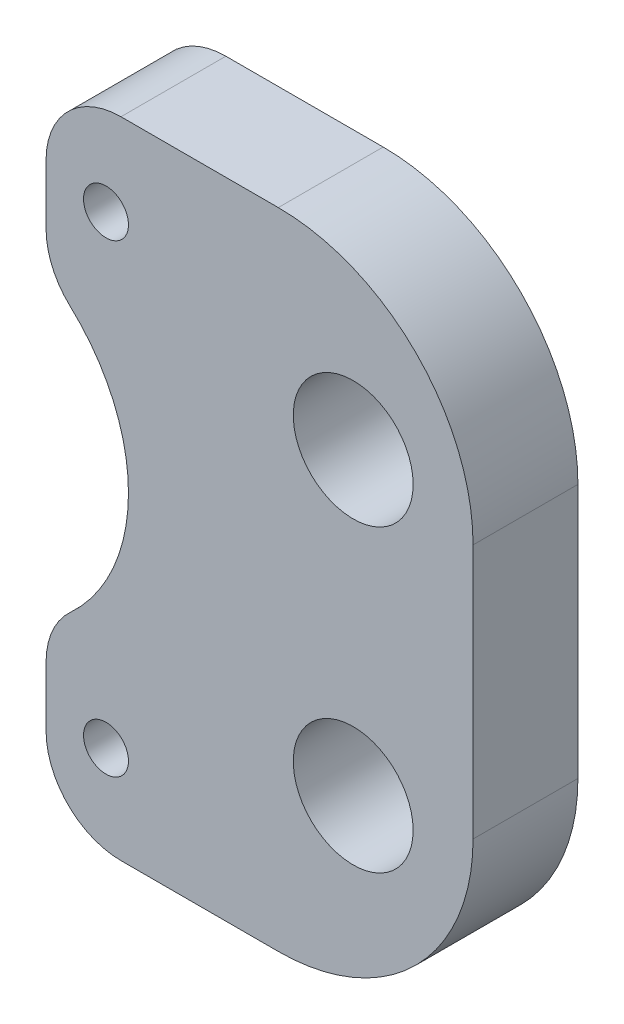
SolidWorks part; units mm, degrees
ref_plane "Alzado" through (0, 0, 0) normal (0, 0, 1) x (1, 0, 0)
ref_plane "Planta" through (0, 0, 0) normal (0, 1, 0) x (1, 0, 0)
ref_plane "Vista lateral" through (0, 0, 0) normal (1, 0, 0) x (0, 0, -1)
sketch "Croquis1" plane through (0, 0, 0) normal (0, 0, 1) x (1, 0, 0)
  line L0 (5, 0) -> (15.5, 0)
  line L1 (28.5, 13) -> (28.5, 30)
  line L2 (15.5, 43) -> (5, 43)
  line L3 (0, 34.02) -> (0, 38)
  line L5 (0, 5) -> (0, 8.98)
  arc A0 (1.6176, 12.6624) -> (1.6176, 30.3376) centre (-6.5, 21.5) ccw
  circle A1 centre (20.5, 31.5) radius 4
  circle A2 centre (20.5, 11.5) radius 4
  circle A3 centre (4, 37) radius 1.5
  circle A4 centre (4, 6) radius 1.5
  arc A5 (1.6176, 30.3376) -> (0, 34.02) centre (5, 34.02) cw
  arc A6 (0, 8.98) -> (1.6176, 12.6624) centre (5, 8.98) cw
  arc A7 (28.5, 13) -> (15.5, 0) centre (15.5, 13) cw
  arc A8 (28.5, 30) -> (15.5, 43) centre (15.5, 30) ccw
  arc A9 (5, 43) -> (0, 38) centre (5, 38) ccw
  arc A10 (0, 5) -> (5, 0) centre (5, 5) ccw
  point P16 (0, 31.5871)
  point P18 (0, 0)
  point P30 (0, 0)
  dimension "D3" = 8
  dimension "D4" = 8
  dimension "D8" = 3
  dimension "D9" = 3
  dimension "D10" = 31
  dimension "D11" = 6
  dimension "D12" = 24
  dimension "D14" = 35
  dimension "D15" = 13
  dimension "D16" = 11.5
  dimension "D13" = 21.5
  dimension "D18" = 5
  dimension "D19" = 5
  dimension "D2" = 20
  dimension "D5" = 8
  dimension "D6" = 28.5
  dimension "D7" = 43
  dimension "D17" = 4
extrude "Saliente-Extruir1" add sketch "Croquis1" along normal blind 7
